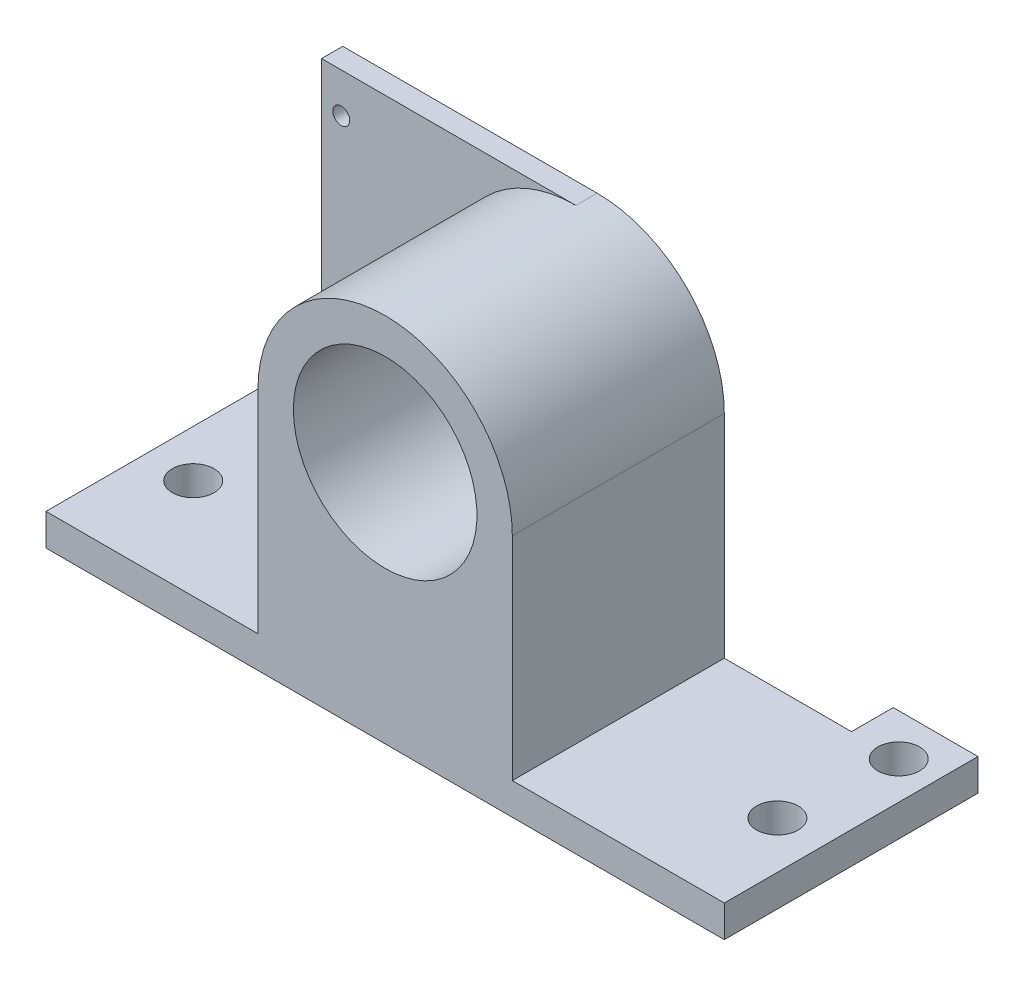
SolidWorks part; units mm, degrees
ref_plane "Front Plane" through (0, 0, 0) normal (0, 0, 1) x (1, 0, 0)
ref_plane "Top Plane" through (0, 0, 0) normal (0, 1, 0) x (1, 0, 0)
ref_plane "Right Plane" through (0, 0, 0) normal (1, 0, 0) x (0, 0, -1)
sketch "Sketch1" plane through (0, 0, 0) normal (0, 0, 1) x (1, 0, 0)
  line L0 (-40.64, -29.21) -> (40.64, -29.21)
  line L1 (-40.64, -25.4) -> (-15.24, -25.4)
  line L2 (-15.24, 0) -> (-15.24, -25.4)
  line L3 (-40.64, -25.4) -> (-40.64, -29.21)
  line L4 (15.24, 0) -> (15.24, -25.4)
  line L5 (40.64, -25.4) -> (40.64, -29.21)
  line L6 (15.24, -25.4) -> (40.64, -25.4)
  line L7 (0, 0) -> (0, 15.24) construction
  circle A0 centre (0, 0) radius 11
  arc A1 (15.24, 0) -> (-15.24, 0) centre (0, 0) ccw
  dimension "D1" = 29.21
  dimension "D5" = 22
  dimension "D2" = 3.81
  dimension "D3" = 25.4
  dimension "D4" = 25.4
  dimension "D6" = 30.48
extrude "Boss-Extrude1" add sketch "Sketch1" along normal blind 30.4
sketch "Sketch2" plane through (0, -25.4, 0) normal (0, 1, 0) x (1, 0, 0)
  line L0 (40.64, 0) -> (15.24, 0) construction
  line L1 (30.48, 0) -> (-30.48, 0)
  line L2 (30.48, 0) -> (30.48, -5)
  line L3 (30.48, -5) -> (-30.48, -5)
  line L4 (-30.48, 0) -> (-30.48, -5)
  line L5 (-40.64, -30.4) -> (-40.64, 0) construction
  line L6 (40.64, -30.4) -> (40.64, 0) construction
  line L7 (-15.24, 0) -> (-40.64, 0) construction
  circle A0 centre (-36.14, -5) radius 2.5
  circle A1 centre (-35, -18.4) radius 2.5
  circle A2 centre (36.14, -5) radius 2.5
  circle A3 centre (35, -18.4) radius 2.5
  dimension "D4" = 5
  dimension "D5" = 5
  dimension "D6" = 4.5
  dimension "D7" = 5.64
  dimension "D8" = 18.4
  dimension "D9" = 4.5
  dimension "D10" = 5.64
  dimension "D11" = 5
  dimension "D12" = 18.4
  dimension "D1" = 5
  dimension "D2" = 10.16
  dimension "D3" = 10.16
extrude "Cut-Extrude1" cut sketch "Sketch2" against normal blind 30.4 and the other way blind 65.4
sketch "Sketch3" plane through (0, 0, 5) normal (0, 0, -1) x (-1, 0, 0)
  line L0 (0, 11) -> (0, 15.24)
  line L1 (30.48, -25.4) -> (0, -25.4)
  line L2 (30.48, -25.4) -> (30.48, 15.24)
  line L3 (30.48, 15.24) -> (0, 15.24)
  line L4 (0, -25.4) -> (0, -11)
  arc A0 (15.24, 0) -> (-15.24, 0) centre (0, 0) ccw construction
  arc A1 (0, -11) -> (0, 11) centre (0, 0) ccw
  circle A2 centre (28.1178, 10.4775) radius 1.016
  circle A3 centre (28.1178, -10.4775) radius 1.016
  dimension "D1" = 2.3622
  dimension "D2" = 2.3622
  dimension "D3" = 20.955
  dimension "D4" = 4.7625
  dimension "D5" = 2.032
extrude "Boss-Extrude2" add sketch "Sketch3" against normal blind 2.54
